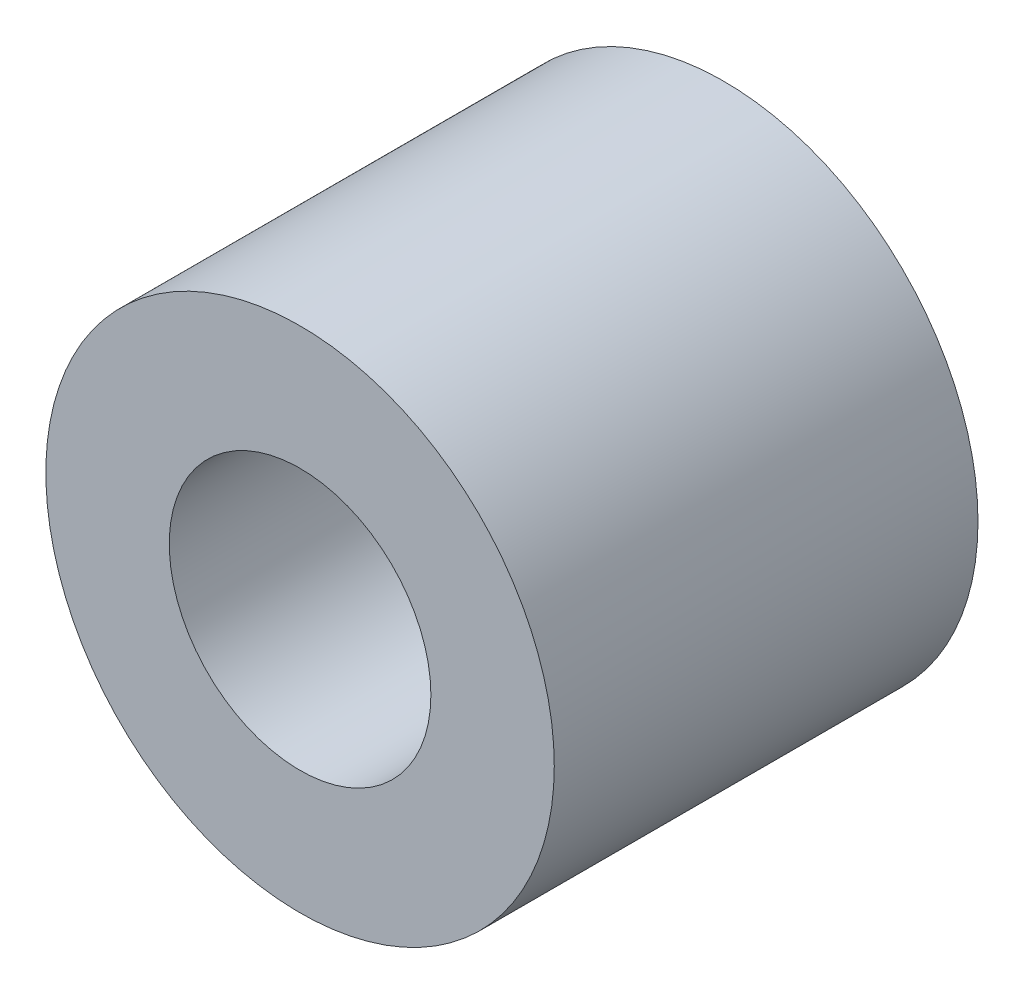
SolidWorks part; units mm, degrees
ref_plane "Front Plane" through (0, 0, 0) normal (0, 0, 1) x (1, 0, 0)
ref_plane "Top Plane" through (0, 0, 0) normal (0, 1, 0) x (1, 0, 0)
ref_plane "Right Plane" through (0, 0, 0) normal (1, 0, 0) x (0, 0, -1)
sketch "Sketch1" plane through (0, 0, 0) normal (0, 0, 1) x (1, 0, 0)
  circle A0 centre (0, 0) radius 6
  circle A1 centre (0, 0) radius 3.0875
  dimension "D1" = 12
  dimension "ID" = 6.175
extrude "Extrude1" add sketch "Sketch1" along normal mid plane 10
sketch "Sketch2" plane through (0, 0, 0) normal (1, 0, 0) x (0, 0, -1)
  line L0 (-5, -3.0875) -> (5, -3.0875) construction
  line L3 (5, 3.0875) -> (-5, 3.0875) construction
  line L5 (-5, -3.0875) -> (5, -3.0875)
  line L6 (5, 3.0875) -> (-5, 3.0875)
sketch "Sketch4" plane through (0, 0, 5) normal (0, 0, 1) x (1, 0, 0)
  line L0 (0, 0) -> (-2.1832, 2.1832)
  line L1 (0, -22) -> (0, 22) construction
  circle A0 centre (0, 0) radius 3.0875 construction
  dimension "D1" = 45
ref_plane "Plane1" through (0, 0, -70) normal (0, 0, 1) x (1, 0, 0)
